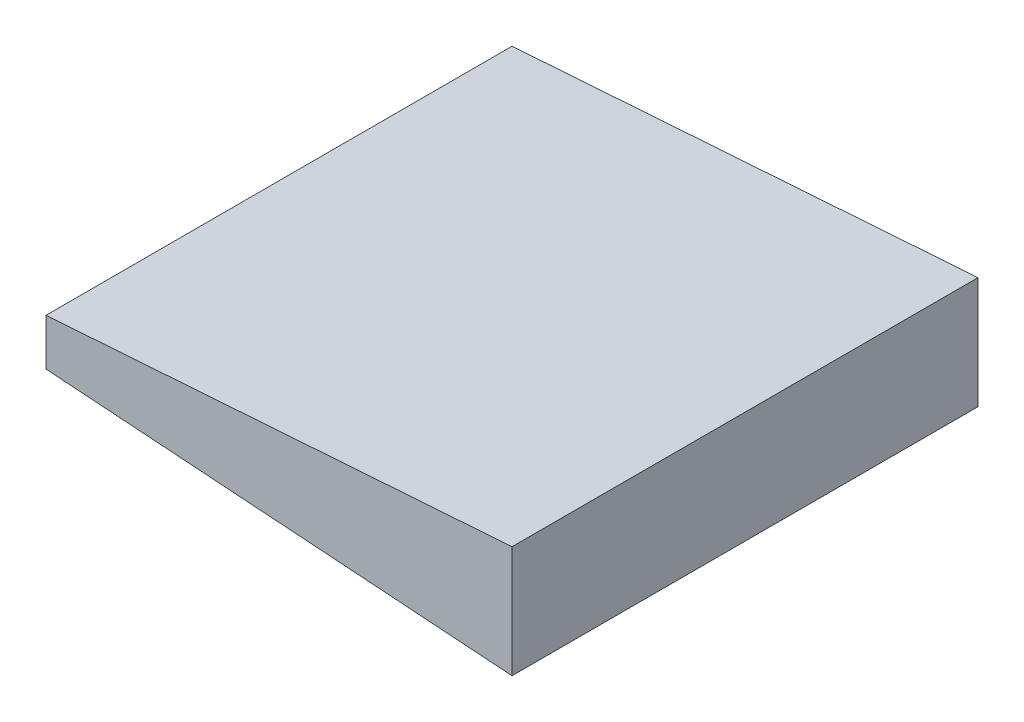
SolidWorks part; units mm, degrees
ref_plane "Front Plane" through (0, 0, 0) normal (0, 0, 1) x (1, 0, 0)
ref_plane "Top Plane" through (0, 0, 0) normal (0, 1, 0) x (1, 0, 0)
ref_plane "Right Plane" through (0, 0, 0) normal (1, 0, 0) x (0, 0, -1)
sketch "Sketch1" plane through (0, 0, 0) normal (0, 0, 1) x (1, 0, 0)
  line L0 (-50, 5) -> (-50, -5)
  line L1 (-50, 5) -> (50, 11.9927)
  line L2 (50, 11.9927) -> (50, -11.9927)
  line L3 (50, -11.9927) -> (-50, -5)
  point P4 (50, 0)
  point P5 (-50, 0)
  dimension "D1" = 50
  dimension "D2" = 50
  dimension "D3" = 10
  dimension "D4" = 8
extrude "Boss-Extrude1" add sketch "Sketch1" along normal mid plane 100
